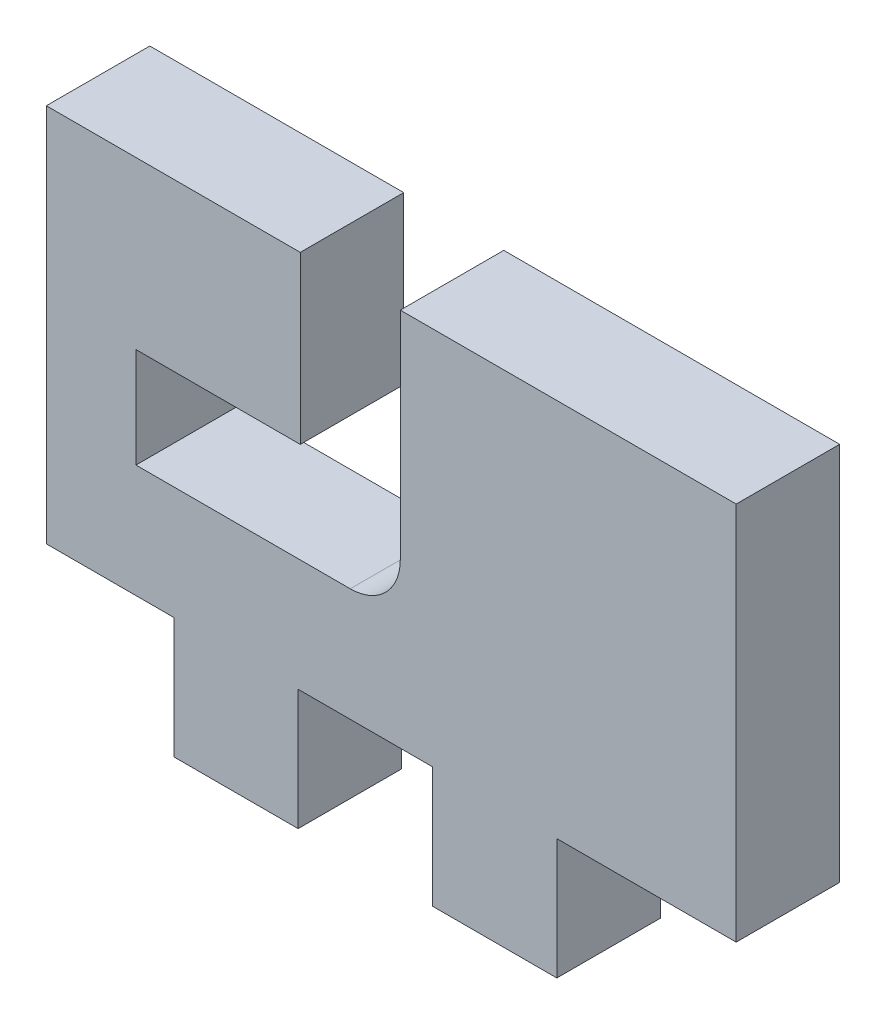
SolidWorks part; units mm, degrees
ref_plane "Front Plane" through (0, 0, 0) normal (0, 0, 1) x (1, 0, 0)
ref_plane "Top Plane" through (0, 0, 0) normal (0, 1, 0) x (1, 0, 0)
ref_plane "Right Plane" through (0, 0, 0) normal (1, 0, 0) x (0, 0, -1)
sketch "Sketch1" plane through (0, 0, 0) normal (0, 0, 1) x (1, 0, 0)
  line L1 (-7.8838, 4.334) -> (12.1162, 4.334)
  line L2 (-7.8838, 4.334) -> (-7.8838, -10.166)
  line L3 (-7.8838, -10.166) -> (12.1162, -10.166)
  line L4 (12.1162, 4.334) -> (12.1162, -10.166)
  dimension "D1" = 20
  dimension "D2" = 14.5
extrude "Boss-Extrude1" add sketch "Sketch1" along normal blind 3
sketch "Sketch2" plane through (0, 0, 3) normal (0, 0, 1) x (1, 0, 0)
  line L0 (-7.8838, -10.166) -> (12.1162, -10.166) construction
  line L1 (-7.8838, -10.166) -> (-4.1838, -10.166)
  line L2 (-7.8838, -10.166) -> (-7.8838, -6.666)
  line L3 (-7.8838, -6.666) -> (-4.1838, -6.666)
  line L4 (-4.1838, -10.166) -> (-4.1838, -6.666)
  line L5 (-0.5838, -10.166) -> (3.3162, -10.166)
  line L6 (-0.5838, -10.166) -> (-0.5838, -6.666)
  line L7 (-0.5838, -6.666) -> (3.3162, -6.666)
  line L8 (3.3162, -10.166) -> (3.3162, -6.666)
  line L9 (12.1162, -10.166) -> (12.1162, 4.334) construction
  line L10 (6.9162, -10.166) -> (12.1162, -10.166)
  line L11 (6.9162, -10.166) -> (6.9162, -6.666)
  line L12 (6.9162, -6.666) -> (12.1162, -6.666)
  line L13 (12.1162, -10.166) -> (12.1162, -6.666)
  dimension "D1" = 3.7
  dimension "D2" = 3.5
  dimension "D3" = 3.6
  dimension "D4" = 3.9
  dimension "D5" = 3.5
  dimension "D6" = 3.6
  dimension "D7" = 3.5
extrude "Cut-Extrude1" cut sketch "Sketch2" against normal blind 3
sketch "Sketch3" plane through (0, 0, 3) normal (0, 0, 1) x (1, 0, 0)
  line L0 (0.928, 4.334) -> (0.928, -1.9382) construction
  line L1 (12.1162, 4.334) -> (-7.8838, 4.334) construction
  line L2 (2.378, 4.334) -> (2.378, -1.9382)
  line L3 (-0.522, 4.334) -> (-0.522, -1.9382)
  arc A0 (2.378, 4.334) -> (-0.522, 4.334) centre (0.928, 4.334) ccw
  arc A1 (-0.522, -1.9382) -> (2.378, -1.9382) centre (0.928, -1.9382) ccw
  point P4 (0.928, 1.1979)
  dimension "D1" = 2.9
extrude "Cut-Extrude2" cut sketch "Sketch3" against normal blind 3
sketch "Sketch4" plane through (0, 0, 3) normal (0, 0, 1) x (1, 0, 0)
  line L4 (0.928, -3.3882) -> (-5.2854, -3.3882)
  line L7 (0.928, -3.3882) -> (0.928, -0.4882)
  line L8 (0.928, -0.4882) -> (-5.2854, -0.4882)
  line L9 (-5.2854, -3.3882) -> (-5.2854, -0.4882)
  arc A4 (-0.522, -1.9382) -> (2.378, -1.9382) centre (0.928, -1.9382) ccw construction
  dimension "D1" = 2.9
extrude "Cut-Extrude3" cut sketch "Sketch4" against normal blind 10
